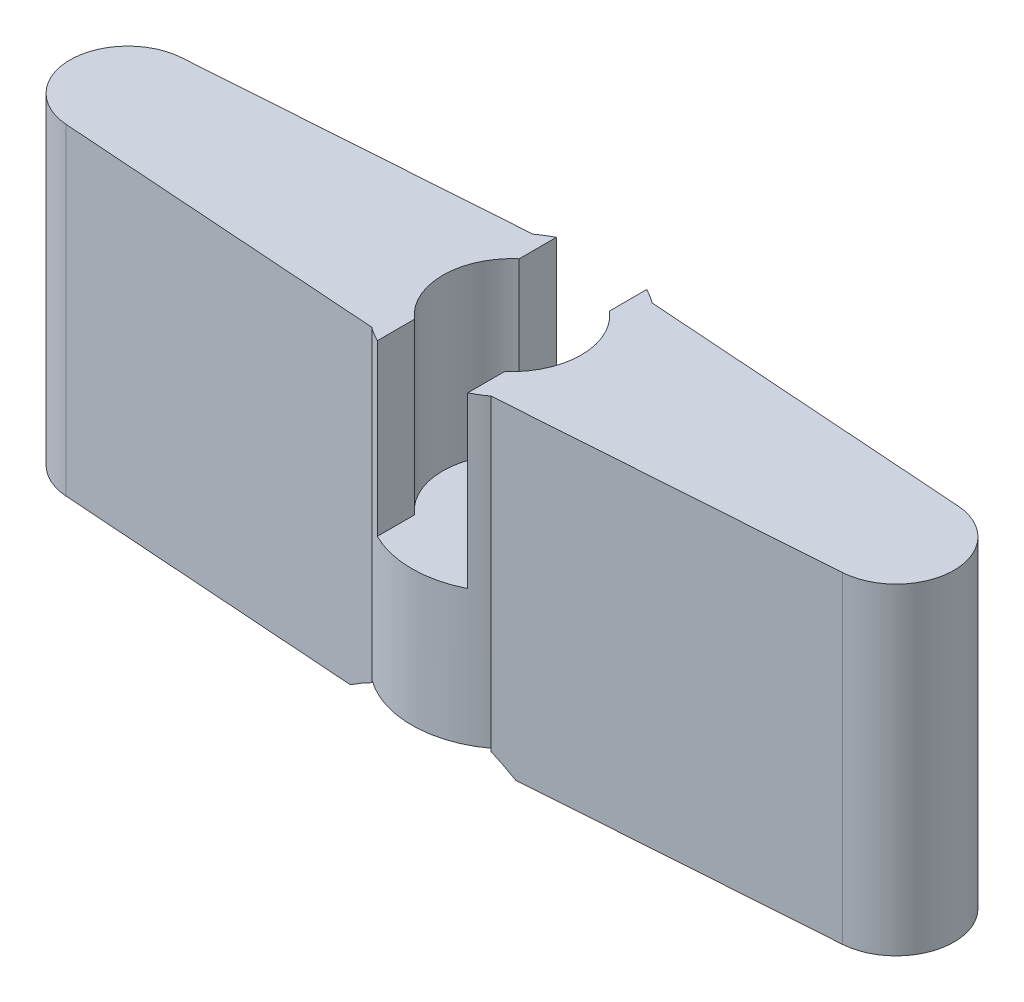
SolidWorks part; units mm, degrees
ref_plane "Front Plane" through (0, 0, 0) normal (0, 0, 1) x (1, 0, 0)
ref_plane "Top Plane" through (0, 0, 0) normal (0, 1, 0) x (1, 0, 0)
ref_plane "Right Plane" through (0, 0, 0) normal (1, 0, 0) x (0, 0, -1)
sketch "Sketch2" plane through (0, 0, 0) normal (0, 1, 0) x (1, 0, 0)
  line L0 (0, 0) -> (-13.6, 0) construction
  line L1 (-13.7421, -2.0451) -> (-2.1121, -2.8534)
  line L2 (-13.7525, -2.1947) -> (-2.1656, -3) construction
  line L3 (-13.7525, 2.1947) -> (-2.1656, 3) construction
  line L4 (0, 3.7) -> (0, -3.7) construction
  line L5 (13.7525, 2.1947) -> (2.1656, 3) construction
  line L6 (13.7525, -2.1947) -> (2.1656, -3) construction
  line L7 (13.7421, -2.0451) -> (2.1121, -2.8534)
  line L8 (13.7421, 2.0451) -> (2.1121, 2.8534)
  line L9 (-13.7421, 2.0451) -> (-2.1121, 2.8534)
  arc A0 (-13.7525, -2.1947) -> (-13.7525, 2.1947) centre (-13.6, 0) cw construction
  arc A2 (-2.1656, -3) -> (2.1656, -3) centre (0, 0) ccw construction
  arc A3 (13.7525, -2.1947) -> (13.7525, 2.1947) centre (13.6, 0) ccw construction
  arc A4 (-2.1656, 3) -> (-3.7, 0) centre (0, 0) ccw construction
  arc A5 (-3.7, 0) -> (-2.1656, -3) centre (0, 0) ccw construction
  arc A6 (2.1656, 3) -> (-2.1656, 3) centre (0, 0) ccw construction
  arc A7 (2.1656, -3) -> (2.1656, 3) centre (0, 0) ccw construction
  arc A8 (-2.1121, -2.8534) -> (2.1121, -2.8534) centre (0, 0) ccw
  arc A9 (13.7421, -2.0451) -> (13.7421, 2.0451) centre (13.6, 0) ccw
  arc A10 (2.1121, 2.8534) -> (-2.1121, 2.8534) centre (0, 0) ccw
  arc A11 (-13.7421, -2.0451) -> (-13.7421, 2.0451) centre (-13.6, 0) cw
  point P0 (0, 3.7)
  point P1 (-15.8, 0)
  point P30 (0, 0)
  dimension "D2" = 7.4
  dimension "D5" = 2.2
  dimension "D1" = 15.8
  dimension "D3" = 0.15
  dimension "D4" = 6
extrude "Boss-Extrude1" add sketch "Sketch2" along normal blind 11.4
sketch "Sketch3" plane through (0, 0, 0) normal (0, -1, 0) x (1, 0, 0)
  arc A0 (-2.1121, -2.8534) -> (2.1121, -2.8534) centre (0, 0) ccw construction
  arc A1 (2.1121, 2.8534) -> (-2.1121, 2.8534) centre (0, 0) ccw construction
  arc A2 (-2.1121, 2.8534) -> (2.1121, 2.8534) centre (0, 0) ccw
  arc A3 (2.1121, 2.8534) -> (-2.1121, 2.8534) centre (0, 0) ccw
extrude "Cut-Extrude1" cut sketch "Sketch3" against normal blind 0.6
sketch "Shaft Key" plane through (0, 11.4, 0) normal (0, 1, 0) x (1, 0, 0)
  line L0 (1.5, -1.809) -> (1.5, -5.35) construction
  line L7 (1.5, -5.35) -> (-1.5, -5.35) construction
  line L8 (-1.5, -5.35) -> (-1.5, -1.809) construction
  line L9 (0, -2.35) -> (0, -5.35) construction
  line L10 (-2.35, 0) -> (2.35, 0) construction
  line L11 (-1.5, 5.35) -> (-1.5, 1.809) construction
  line L12 (1.5, 5.35) -> (-1.5, 5.35) construction
  line L13 (1.5, 1.809) -> (1.5, 5.35) construction
  line L14 (0, 0) -> (0, -2.35) construction
  line L15 (1.6, -1.8554) -> (1.6, -5.45)
  line L16 (1.6, -5.45) -> (-1.6, -5.45)
  line L17 (-1.6, -5.45) -> (-1.6, -1.8554)
  line L18 (-1.6, 5.45) -> (-1.6, 1.8554)
  line L19 (1.6, 5.45) -> (-1.6, 5.45)
  line L20 (1.6, 1.8554) -> (1.6, 5.45)
  arc A0 (1.5, -1.809) -> (1.5, 1.809) centre (0, 0) ccw construction
  arc A1 (-1.5, -1.809) -> (0, -2.35) centre (0, 0) ccw construction
  arc A2 (0, -2.35) -> (1.5, -1.809) centre (0, 0) ccw construction
  arc A3 (-1.5, 1.809) -> (-1.5, -1.809) centre (0, 0) ccw construction
  arc A4 (1.5, 1.809) -> (-1.5, 1.809) centre (0, 0) ccw construction
  arc A5 (-1.6, 1.8554) -> (-1.6, -1.8554) centre (0, 0) ccw
  arc A6 (1.6, -1.8554) -> (1.6, 1.8554) centre (0, 0) ccw
  point P11 (0, 0)
  dimension "D1" = 4.7
  dimension "D2" = 3
  dimension "D3" = 3
  dimension "D4" = 0.1
chamfer "Chamfer1" distance 0.5 angle 45 1 edges at (3.55, 0, 0)
extrude "Cut-Extrude2" cut sketch "Shaft Key" against normal blind 6
